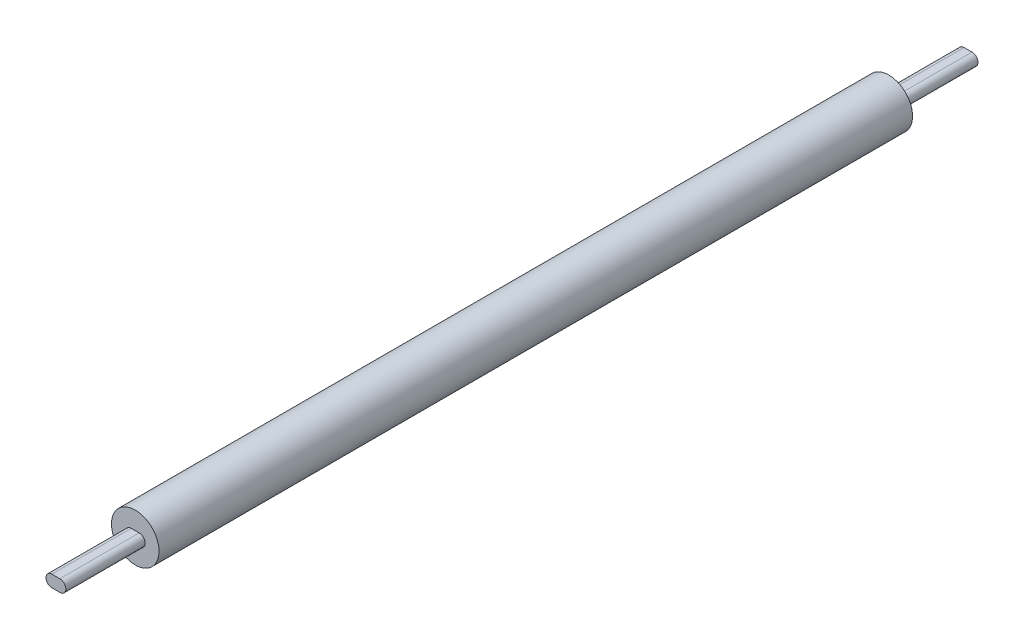
SolidWorks part; units mm, degrees
ref_plane "Front Plane" through (0, 0, 0) normal (0, 0, 1) x (1, 0, 0)
ref_plane "Top Plane" through (0, 0, 0) normal (0, 1, 0) x (1, 0, 0)
ref_plane "Right Plane" through (0, 0, 0) normal (1, 0, 0) x (0, 0, -1)
sketch "Esquisse1" plane through (0, 0, 0) normal (0, 0, 1) x (1, 0, 0)
  circle A0 centre (0, 0) radius 6
  dimension "D1" = 12
extrude "Boss.-Extru.1" add sketch "Esquisse1" along normal blind 190
sketch "Esquisse2" plane through (0, 0, 190) normal (0, 0, 1) x (1, 0, 0)
  line L0 (-1, 0) -> (1, 0) construction
  line L1 (-1, 1.5) -> (1, 1.5)
  line L2 (-1, -1.5) -> (1, -1.5)
  arc A0 (-1, 1.5) -> (-1, -1.5) centre (-1, 0) ccw
  arc A1 (1, -1.5) -> (1, 1.5) centre (1, 0) ccw
  circle A2 centre (0, 0) radius 6 construction
  point P3 (0, 0)
  dimension "D2" = 1.5
  dimension "D1" = 2
extrude "Boss.-Extru.2" add sketch "Esquisse2" along normal blind 20
sketch "Esquisse3" plane through (0, 0, 0) normal (0, 0, -1) x (-1, 0, 0)
  line L0 (-1, 0) -> (1, 0) construction
  line L1 (-1, 1.5) -> (1, 1.5)
  line L2 (-1, -1.5) -> (1, -1.5)
  arc A0 (-1, 1.5) -> (-1, -1.5) centre (-1, 0) ccw
  arc A1 (1, -1.5) -> (1, 1.5) centre (1, 0) ccw
  circle A2 centre (0, 0) radius 6 construction
  point P4 (0, 0)
  dimension "D2" = 1.5
  dimension "D1" = 2
extrude "Boss.-Extru.3" add sketch "Esquisse3" along normal blind 20
